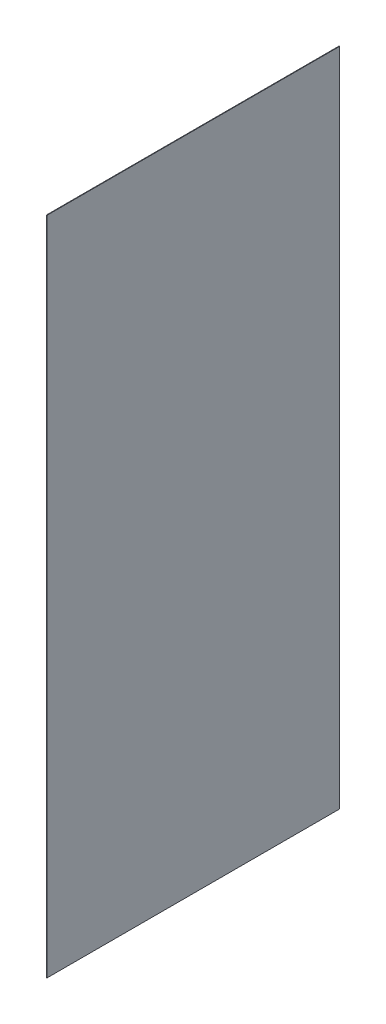
SolidWorks part; units mm, degrees
ref_plane "Front Plane" through (0, 0, 0) normal (0, 0, 1) x (1, 0, 0)
ref_plane "Top Plane" through (0, 0, 0) normal (0, 1, 0) x (1, 0, 0)
ref_plane "Right Plane" through (0, 0, 0) normal (1, 0, 0) x (0, 0, -1)
other "Configuration Table"
sketch "Sketch1" plane through (0, 0, 0) normal (0, 0, 1) x (1, 0, 0)
  line L1 (1398.5, 120) -> (1400, 120)
  line L2 (1398.5, 120) -> (1398.5, 1970)
  line L3 (1398.5, 1970) -> (1400, 1970)
  line L4 (1400, 120) -> (1400, 1970)
extrude "STORE_dis_yan_sag_1" add sketch "Sketch1" against normal blind 820 separate body
